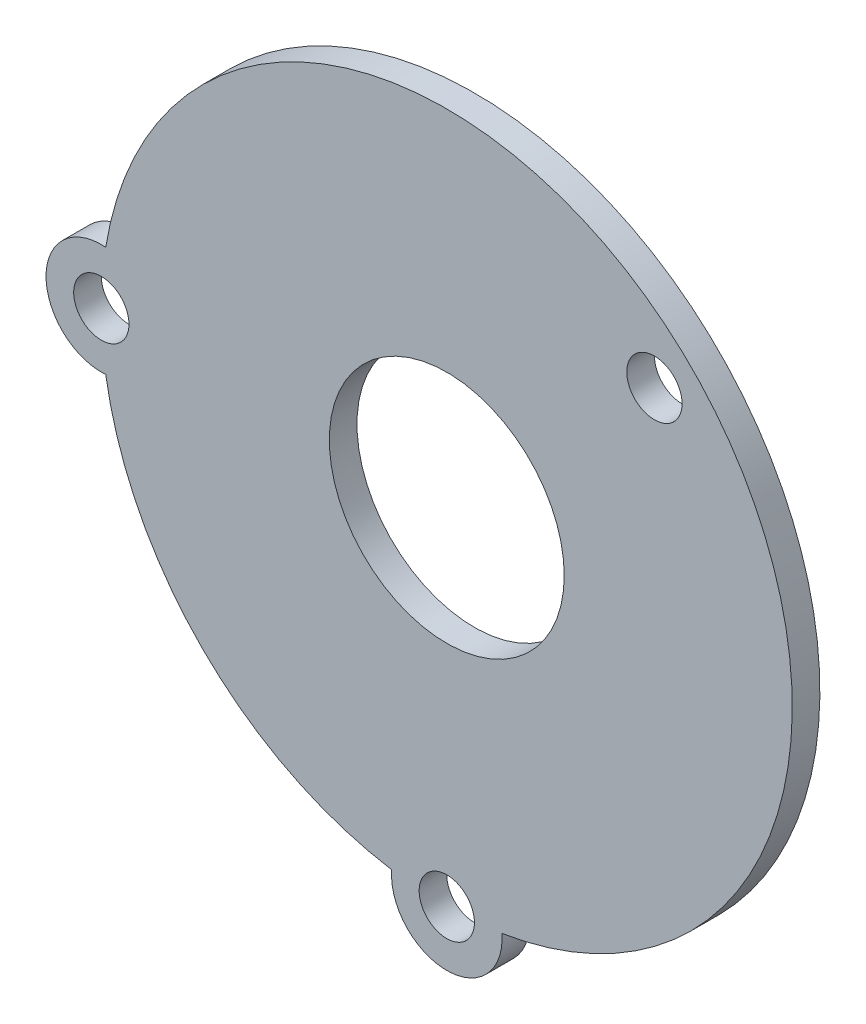
SolidWorks part; units mm, degrees
ref_plane "前视基准面" through (0, 0, 0) normal (0, 0, 1) x (1, 0, 0)
ref_plane "上视基准面" through (0, 0, 0) normal (0, 1, 0) x (1, 0, 0)
ref_plane "右视基准面" through (0, 0, 0) normal (1, 0, 0) x (0, 0, -1)
sketch "Sketch1" plane through (0, 0, 0) normal (0, 0, 1) x (1, 0, 0)
  line L0 (-32.6424, 0) -> (-23, 0) construction
  line L1 (7.3612, 4.25) -> (0, 0) construction
  line L2 (-21, 0) -> (0, 0) construction
  line L3 (17.6777, 17.6777) -> (12.3744, 12.3744) construction
  circle A1 centre (0, 0) radius 8.5
  circle A2 centre (0, 0) radius 17.5 construction
  circle A3 centre (0, -25) radius 2
  circle A7 centre (15.026, 15.026) radius 2
  arc A8 (-15.0351, 19.9736) -> (-20.3231, 14.5593) centre (0, 0) ccw
  arc A10 (-3.9872, -24.68) -> (3.9872, -24.68) centre (0, -25) ccw
  circle A11 centre (-25, 0) radius 2
  arc A12 (-20.3231, 14.5593) -> (-24.68, 3.9872) centre (0, 0) ccw
  circle A13 centre (0, -25) radius 4 construction
  arc A14 (-1.9984, -24.92) -> (1.9984, -24.92) centre (0, 0) ccw
  arc A15 (3.9872, -24.68) -> (-15.0351, 19.9736) centre (0, 0) ccw
  arc A16 (-24.68, 3.9872) -> (-24.68, -3.9872) centre (-25, 0) ccw
  circle A17 centre (-25, 0) radius 4 construction
  arc A19 (-24.68, -3.9872) -> (-3.9872, -24.68) centre (0, 0) ccw
  point P9 (15.026, 15.026)
  point P30 (15.026, 15.026)
  dimension "D1" = 2
  dimension "D2" = 2
  dimension "D3" = 25
  dimension "D4" = 4
  dimension "D5" = 35
extrude "Boss-Extrude1" add sketch "Sketch1" along normal blind 2 contours A10 A15 A8 A12 A1 A3 A11 A7
